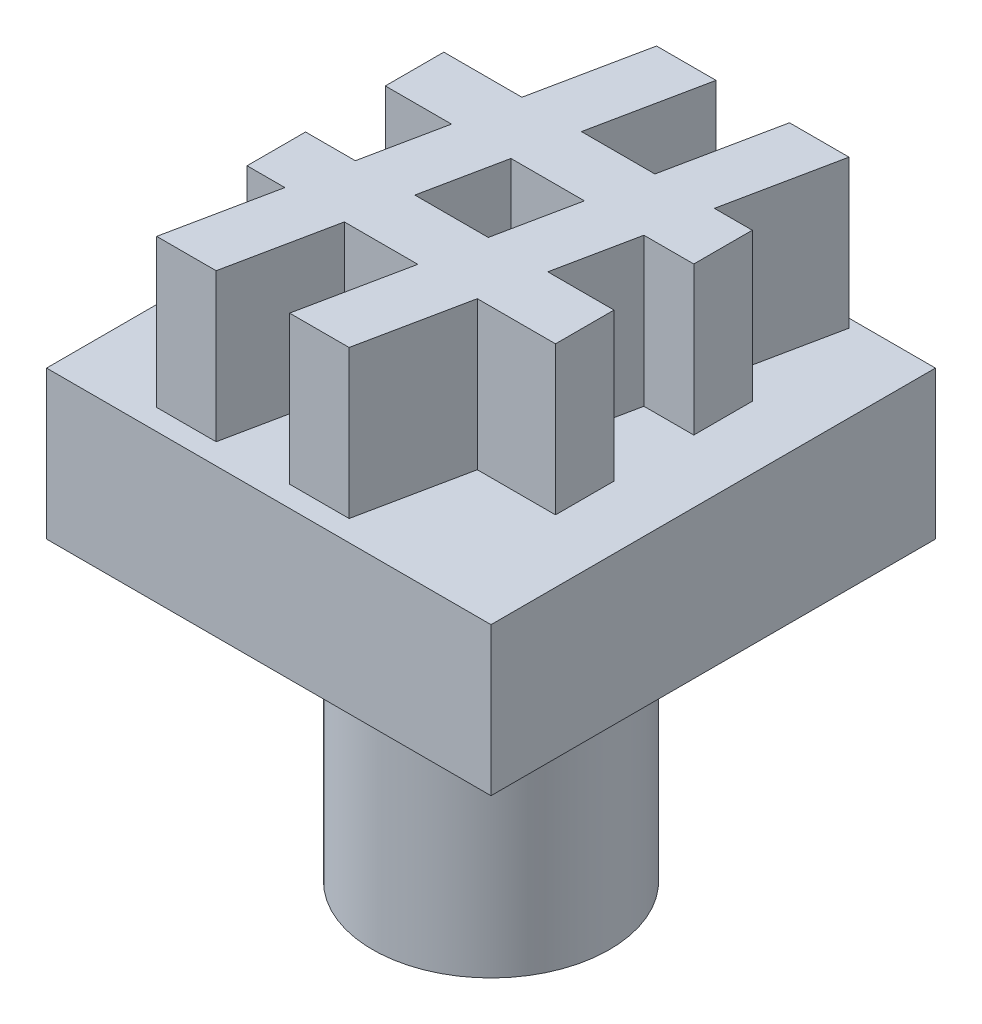
SolidWorks part; units mm, degrees
ref_plane "Front Plane" through (0, 0, 0) normal (0, 0, 1) x (1, 0, 0)
ref_plane "Top Plane" through (0, 0, 0) normal (0, 1, 0) x (1, 0, 0)
ref_plane "Right Plane" through (0, 0, 0) normal (1, 0, 0) x (0, 0, -1)
sketch "Sketch1" plane through (0, 0, 0) normal (0, 1, 0) x (1, 0, 0)
  line L1 (7.5, -7.5) -> (-7.5, -7.5)
  line L2 (7.5, -7.5) -> (7.5, 7.5)
  line L3 (7.5, 7.5) -> (-7.5, 7.5)
  line L4 (-7.5, -7.5) -> (-7.5, 7.5)
  line L5 (7.5, -7.5) -> (-7.5, 7.5) construction
  line L6 (7.5, 7.5) -> (-7.5, -7.5) construction
  point P0 (0, 0)
  dimension "D1" = 15
  dimension "D2" = 15
extrude "Boss-Extrude1" add sketch "Sketch1" along normal blind 5
sketch "Sketch2" plane through (0, 5, 0) normal (0, 1, 0) x (1, 0, 0)
  text T0 "#" font "Arial" height 14
extrude "Boss-Extrude2" add sketch "Sketch2" along normal blind 5
sketch "Sketch3" plane through (0, 0, 0) normal (0, -1, 0) x (1, 0, 0)
  circle A0 centre (0, 0) radius 4
  dimension "D1" = 8
extrude "Boss-Extrude3" add sketch "Sketch3" along normal blind 10
